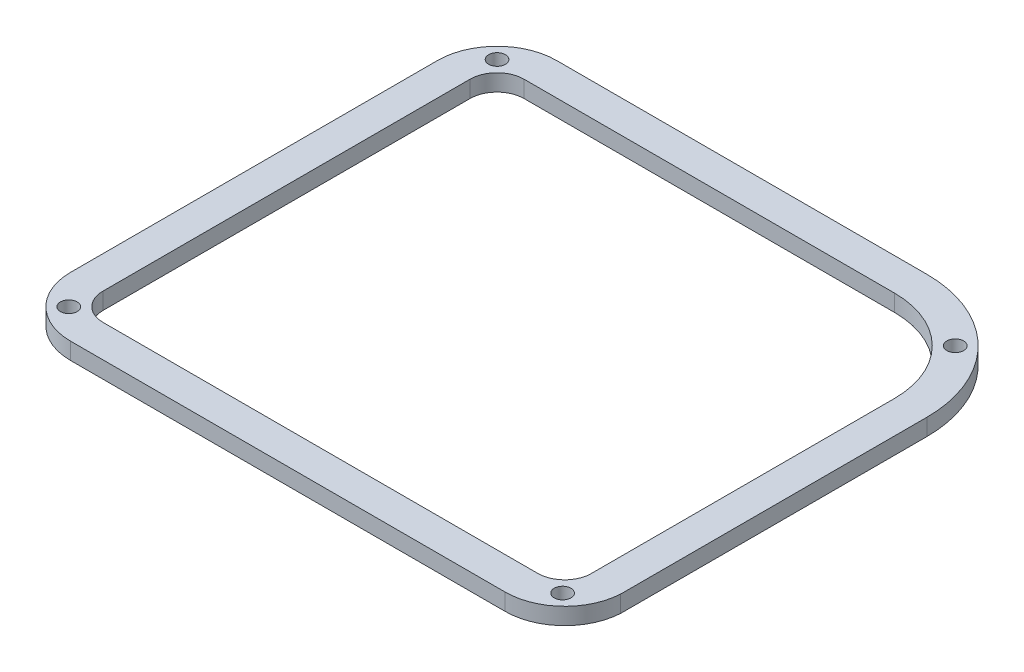
SolidWorks part; units mm, degrees
material "PMMA"
ref_plane "Front Plane" through (0, 0, 0) normal (0, 0, 1) x (1, 0, 0)
ref_plane "Top Plane" through (0, 0, 0) normal (0, 1, 0) x (1, 0, 0)
ref_plane "Right Plane" through (0, 0, 0) normal (1, 0, 0) x (0, 0, -1)
sketch "Sketch1" plane through (0, 0, 0) normal (0, 1, 0) x (1, 0, 0)
  line L0 (-39.7107, 45.6014) -> (28.7393, 45.6014)
  line L1 (51.6193, 22.7214) -> (51.6193, -33.9106)
  line L2 (-39.7107, -44.2386) -> (40.6398, -44.2386)
  line L3 (-50.7107, 34.6014) -> (-50.7107, -33.2386)
  line L4 (-39.7107, 39.6014) -> (28.7393, 39.6014)
  line L5 (45.6193, 22.7214) -> (45.6193, -33.6914)
  line L6 (-39.7107, -38.2386) -> (40.6398, -38.2386)
  line L7 (-44.7107, 34.6014) -> (-44.7107, -33.2386)
  line L8 (-43.2463, 38.1369) -> (-47.4889, 42.3796) construction
  line L9 (-43.2463, -36.7741) -> (-47.4889, -41.0168) construction
  line L10 (44.0114, -36.9308) -> (48.1766, -41.2509) construction
  line L11 (40.6752, 34.6574) -> (44.9179, 38.9) construction
  arc A0 (51.6193, 22.7214) -> (28.7393, 45.6014) centre (28.7393, 22.7214) ccw
  arc A1 (51.6193, -33.9106) -> (40.6398, -44.2386) centre (40.6398, -33.2386) cw
  arc A2 (-50.7107, -33.2386) -> (-39.7107, -44.2386) centre (-39.7107, -33.2386) ccw
  arc A3 (-39.7107, 45.6014) -> (-50.7107, 34.6014) centre (-39.7107, 34.6014) ccw
  arc A4 (45.6193, 22.7214) -> (28.7393, 39.6014) centre (28.7393, 22.7214) ccw
  arc A5 (45.6193, -33.6914) -> (40.6398, -38.2386) centre (40.6398, -33.2386) cw
  arc A6 (-44.7107, -33.2386) -> (-39.7107, -38.2386) centre (-39.7107, -33.2386) ccw
  arc A7 (-39.7107, 39.6014) -> (-44.7107, 34.6014) centre (-39.7107, 34.6014) ccw
  circle A8 centre (-45.3676, 40.2582) radius 1.55
  circle A9 centre (-45.3676, -38.8955) radius 1.55
  circle A10 centre (46.094, -39.0908) radius 1.55
  circle A11 centre (42.7965, 36.7787) radius 1.55
  dimension "D4" = 3.1
  dimension "D1" = 89.84
  dimension "D2" = 102.33
  dimension "D3" = 6
extrude "Boss-Extrude1" add sketch "Sketch1" along normal blind 3.1
